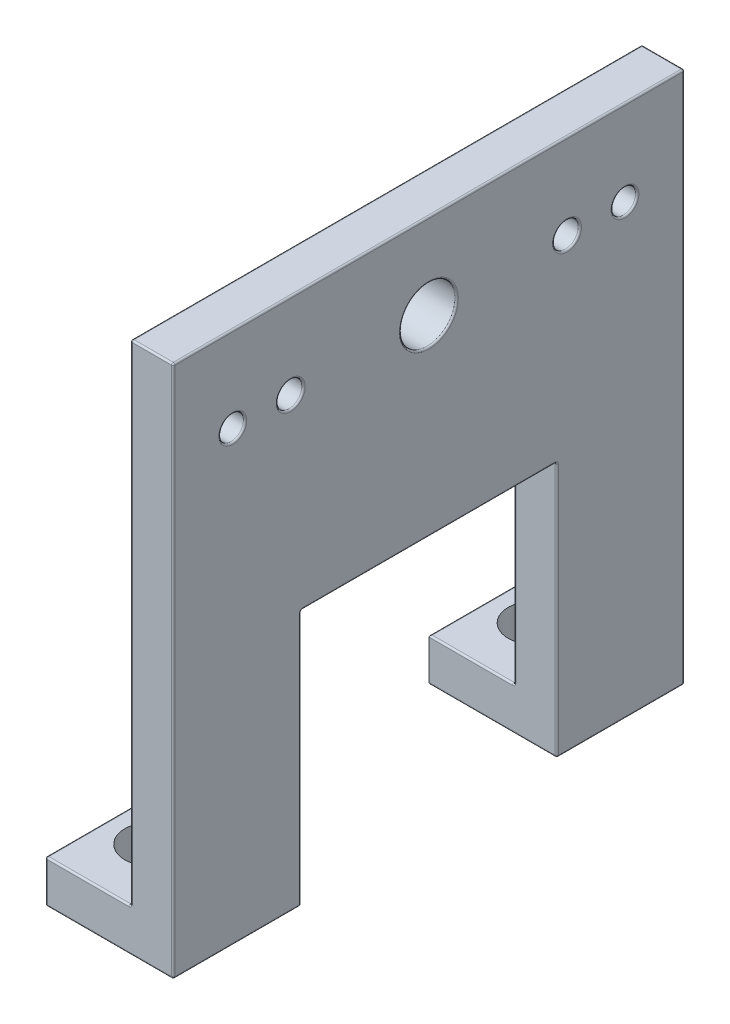
SolidWorks part; units mm, degrees
ref_plane "Front Plane" through (0, 0, 0) normal (0, 0, 1) x (1, 0, 0)
ref_plane "Top Plane" through (0, 0, 0) normal (0, 1, 0) x (1, 0, 0)
ref_plane "Right Plane" through (0, 0, 0) normal (1, 0, 0) x (0, 0, -1)
sketch "Sketch1" plane through (0, 0, 0) normal (0, 0, 1) x (1, 0, 0)
  line L1 (0, 0) -> (15, 0)
  line L2 (0, 0) -> (0, 5)
  line L3 (0, 5) -> (10, 5)
  line L6 (12.5, 0) -> (12.5, 62.531) construction
  line L7 (15, 62.531) -> (10, 62.531)
  line L8 (10, 5) -> (10, 62.531)
  line L10 (15, 5) -> (15, 62.531)
  line L11 (15, 5) -> (15, 0)
  dimension "D1" = 5
  dimension "D2" = 5
  dimension "D3" = 57.531
  dimension "D4" = 15
extrude "Boss-Extrude1" add sketch "Sketch1" along normal blind 60
sketch "Sketch2" plane through (15, 0, 0) normal (1, 0, 0) x (0, 0, -1)
  line L4 (0, 0) -> (0, 62.531)
  line L5 (0, 62.531) -> (-60, 62.531)
  line L6 (-60, 62.531) -> (-60, 0)
  line L7 (-60, 0) -> (0, 0)
  line L8 (0, 0) -> (0, 62.531) construction
  line L9 (0, 62.531) -> (-60, 62.531) construction
  line L10 (-60, 62.531) -> (-60, 0) construction
  line L12 (0, 0) -> (0, 62.531)
  line L13 (0, 62.531) -> (-60, 62.531)
  line L14 (-60, 62.531) -> (-60, 0)
  line L15 (-60, 0) -> (0, 0)
  line L20 (0, 0) -> (0, 62.531) construction
  line L21 (0, 62.531) -> (-60, 62.531) construction
  line L22 (-60, 62.531) -> (-60, 0) construction
  line L23 (-60, 0) -> (0, 0) construction
  circle A0 centre (-30, 52.531) radius 3.25
  circle A1 centre (-6.9875, 52.531) radius 1.435 construction
  circle A2 centre (-13.785, 52.531) radius 1.5 construction
  circle A3 centre (-46.215, 52.531) radius 1.5 construction
  circle A4 centre (-53.0125, 52.531) radius 1.435 construction
  circle A5 centre (-6.9875, 52.531) radius 1.435
  circle A6 centre (-13.785, 52.531) radius 1.5
  circle A7 centre (-46.215, 52.531) radius 1.5
  circle A8 centre (-53.0125, 52.531) radius 1.435
  point P2 (-30, 62.531)
  point P4 (-60, 31.2655)
  point P6 (-30, 52.531)
  dimension "D4" = 6.5
  dimension "D2" = 0
  dimension "D3" = 10
  dimension "D1" = 0
extrude "Cut-Extrude1" cut sketch "Sketch2" against normal through all
sketch "Sketch3" plane through (0, 0, 0) normal (0, 0, -1) x (-1, 0, 0)
  line L0 (-15, 30) -> (-10, 30)
  line L6 (0, 0) -> (0, 5)
  line L7 (0, 5) -> (-10, 5)
  line L8 (-10, 5) -> (-10, 62.531)
  line L9 (-10, 62.531) -> (-15, 62.531)
  line L10 (-15, 62.531) -> (-15, 0)
  line L11 (-15, 0) -> (0, 0)
  line L12 (0, 0) -> (0, 5)
  line L13 (0, 5) -> (-10, 5)
  line L14 (-10, 5) -> (-10, 30)
  line L16 (-15, 30) -> (-15, 0)
  line L17 (-15, 0) -> (0, 0)
  dimension "D2" = 30
  dimension "D1" = 0
extrude "Cut-Extrude2" cut sketch "Sketch3" against normal blind 30 from offset 15 offset against normal yes
fillet "Fillet16" radius 0.2 44 edges at (5, 5, 15) (0, 5, 7.5) (0, 5, 52.5) (5, 5, 45) (12.5, 30, 45) (12.5, 30, 15) (0, 0, 52.5) (7.5, 0, 45) (0, 0, 7.5) (7.5, 0, 15) (5, 5, 60) (12.5, 62.531, 60) (7.5, 0, 60) (0, 2.5, 60) (7.5, 0, 0) (12.5, 62.531, 0) (5, 5, 0) (0, 2.5, 0) (15, 0, 52.5) (15, 31.2655, 60) (15, 62.531, 30) (15, 31.2655, 0) (15, 0, 7.5) (15, 15, 15) (15, 30, 30) (15, 15, 45) (15, 53.966, 53.0125) (15, 54.031, 46.215) (15, 54.031, 13.785) (15, 53.966, 6.9875) (15, 55.781, 30) (10, 30, 30) (10, 17.5, 15) (10, 5, 7.5) (10, 33.7655, 0) (10, 62.531, 30) (10, 33.7655, 60) (10, 5, 52.5) (10, 17.5, 45) (10, 53.966, 53.0125) (10, 54.031, 46.215) (10, 54.031, 13.785) (10, 53.966, 6.9875) (10, 55.781, 30)
sketch "Sketch4" plane through (0, 5, 0) normal (0, 1, 0) x (1, 0, 0)
  line L4 (0.2, -0.2) -> (0.2, -14.8)
  line L5 (0.2, -14.8) -> (9.8, -14.8)
  line L6 (9.8, -14.8) -> (9.8, -0.2)
  line L7 (9.8, -0.2) -> (0.2, -0.2)
  line L8 (0.2, -0.2) -> (0.2, -14.8) construction
  line L9 (0.2, -14.8) -> (9.8, -14.8) construction
  line L10 (9.8, -14.8) -> (9.8, -0.2) construction
  line L11 (9.8, -0.2) -> (0.2, -0.2) construction
  line L12 (9.8, -45.2) -> (0.2, -45.2)
  line L13 (0.2, -45.2) -> (0.2, -59.8)
  line L14 (0.2, -59.8) -> (9.8, -59.8)
  line L15 (9.8, -59.8) -> (9.8, -45.2)
  line L16 (9.8, -45.2) -> (0.2, -45.2) construction
  line L17 (0.2, -45.2) -> (0.2, -59.8) construction
  line L18 (0.2, -59.8) -> (9.8, -59.8) construction
  line L19 (9.8, -59.8) -> (9.8, -45.2) construction
  circle A0 centre (5, -7.5) radius 3.175
  circle A1 centre (5, -52.5) radius 3.175
  point P6 (9.8, -7.5)
  point P8 (5, -0.2)
  point P10 (9.8, -52.5)
  point P11 (5, -45.2)
  dimension "D3" = 6.35
  dimension "D1" = 0
  dimension "D2" = 0
extrude "Cut-Extrude3" cut sketch "Sketch4" against normal through all
